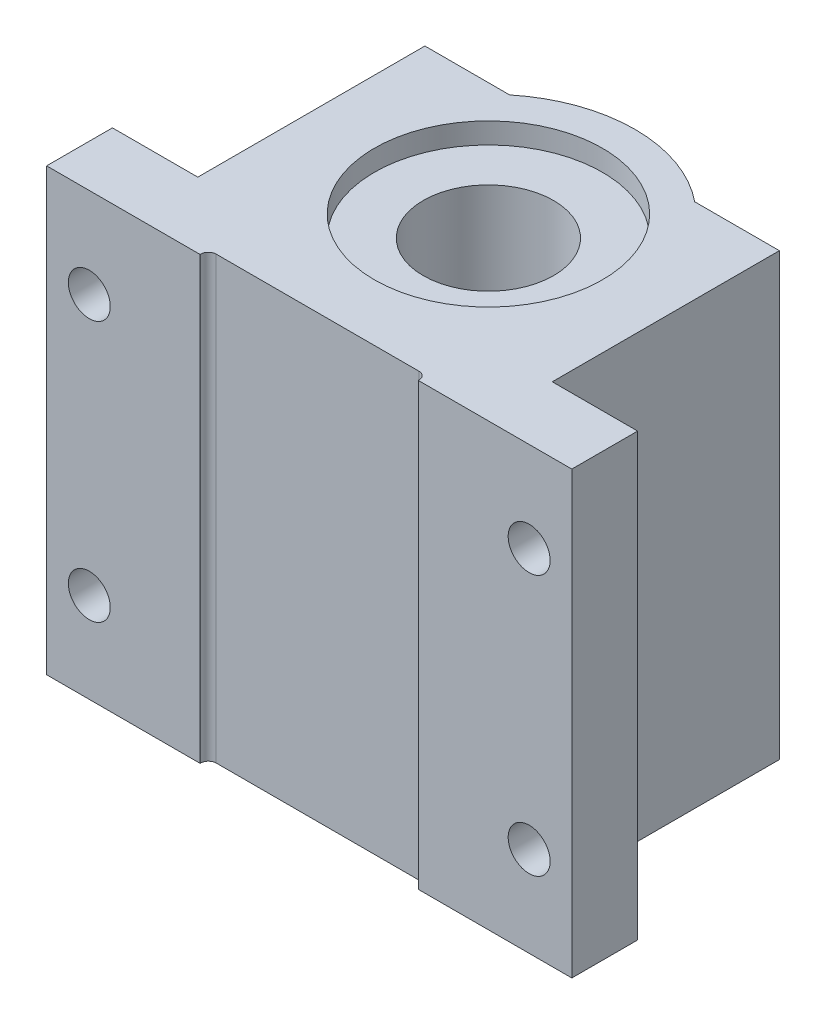
SolidWorks part; units mm, degrees
ref_plane "Front Plane" through (0, 0, 0) normal (0, 0, 1) x (1, 0, 0)
ref_plane "Top Plane" through (0, 0, 0) normal (0, 1, 0) x (1, 0, 0)
ref_plane "Right Plane" through (0, 0, 0) normal (1, 0, 0) x (0, 0, -1)
sketch "Sketch1" plane through (0, 0, 0) normal (0, 1, 0) x (1, 0, 0)
  line L0 (-41.7291, -23.8487) -> (-41.7291, -23.8995)
  line L1 (-5.5024, -23.8995) -> (-5.5024, -17.486)
  line L2 (-5.5024, -17.486) -> (-13.8209, -17.486)
  line L3 (-13.8209, -17.486) -> (-13.8209, 4.6457)
  line L4 (-13.8209, 4.6457) -> (-22.0759, 4.6457)
  line L5 (-31.0929, -6.437) -> (-31.0929, -23.8995) construction
  line L6 (-31.0929, -6.437) -> (-31.0929, 38.656) construction
  line L7 (-20.4566, -23.8995) -> (-5.5024, -23.8995)
  line L8 (-41.7291, -23.8995) -> (-56.6834, -23.8995)
  line L9 (-48.3649, 4.6457) -> (-40.1099, 4.6457)
  line L10 (-48.3649, -17.486) -> (-48.3649, 4.6457)
  line L11 (-40.9671, -23.0867) -> (-21.2186, -23.0867)
  line L12 (-20.4566, -23.8487) -> (-20.4566, -23.8995)
  line L13 (-56.6834, -17.486) -> (-48.3649, -17.486)
  line L14 (-56.6834, -23.8995) -> (-56.6834, -17.486)
  arc A0 (-22.0759, 4.6457) -> (-40.1099, 4.6457) centre (-31.0929, -6.437) ccw
  circle A1 centre (-31.0929, -6.437) radius 6.35
  arc A2 (-20.4566, -23.8487) -> (-21.2186, -23.0867) centre (-21.2186, -23.8487) ccw
  arc A3 (-41.7291, -23.8487) -> (-40.9671, -23.0867) centre (-40.9671, -23.8487) cw
  point P13 (-31.0929, -23.0867)
  point P15 (-31.0929, -23.8995)
  dimension "D7" = 12.7
  dimension "D1" = 0.762
  dimension "D2" = 6.4135
  dimension "D3" = 51.181
  dimension "D4" = 34.544
  dimension "D5" = 8.255
  dimension "D6" = 0.8128
  dimension "D8" = 21.2725
extrude "Boss-Extrude1" add sketch "Sketch1" along normal blind 42.9514
sketch "Sketch2" plane through (0, 42.9514, 0) normal (0, 1, 0) x (1, 0, 0)
  circle A0 centre (-31.0929, -6.437) radius 11.1125
  arc A1 (-22.0759, 4.6457) -> (-40.1099, 4.6457) centre (-31.0929, -6.437) ccw construction
  dimension "D1" = 3.175
extrude "Cut-Extrude1" cut sketch "Sketch2" against normal blind 2.032
sketch "Sketch3" plane through (0, 0, 0) normal (0, -1, 0) x (1, 0, 0)
  circle A0 centre (-31.0929, 6.437) radius 11.1125
  arc A1 (-40.1099, -4.6457) -> (-22.0759, -4.6457) centre (-31.0929, 6.437) ccw construction
  dimension "D1" = 3.175
extrude "Cut-Extrude2" cut sketch "Sketch3" against normal blind 2.032
sketch "Sketch8" plane through (0, 0, 17.486) normal (0, 0, -1) x (-1, 0, 0)
  line L0 (56.6834, 21.4757) -> (5.5024, 21.4757) construction
  line L1 (56.6834, 42.9514) -> (56.6834, 0) construction
  line L2 (5.5024, 42.9514) -> (5.5024, 0) construction
  line L3 (31.0929, 21.4757) -> (31.0929, 64.8801) construction
  circle A0 centre (52.5241, 8.7757) radius 2.0447
  circle A1 centre (52.5241, 34.1757) radius 2.0447
  circle A2 centre (9.6616, 8.7757) radius 2.0447
  circle A3 centre (9.6616, 34.1757) radius 2.0447
  dimension "D3" = 4.0894
  dimension "D1" = 25.4
  dimension "D2" = 42.8625
extrude "Cut-Extrude3" cut sketch "Sketch8" against normal through all
